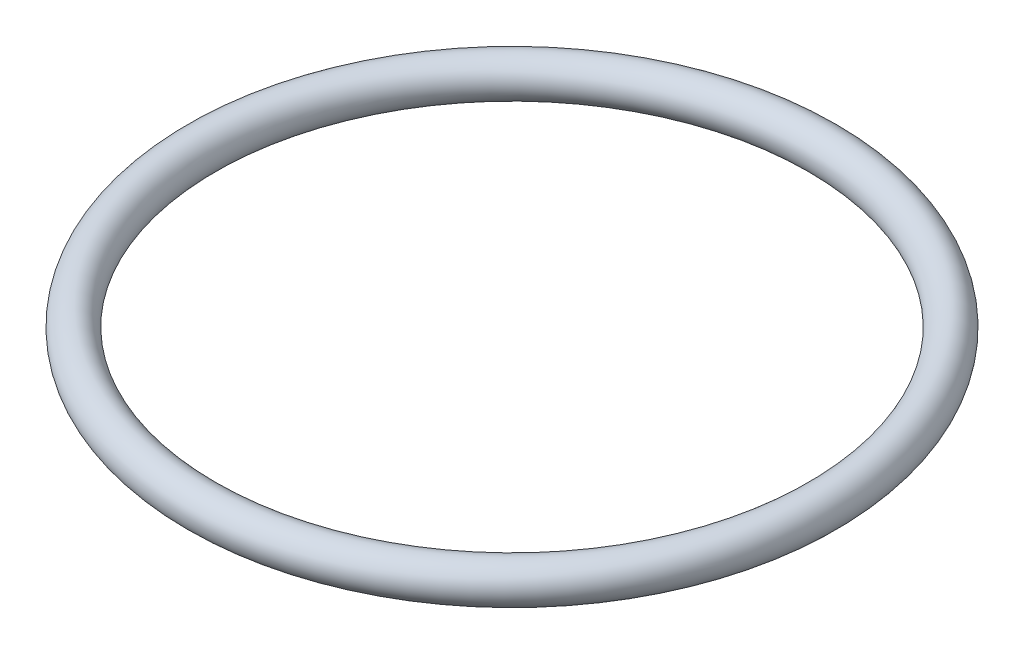
SolidWorks part; units mm, degrees
material "Polybutadiene (PB)"
ref_plane "Front Plane" through (0, 0, 0) normal (0, 0, 1) x (1, 0, 0)
ref_plane "Top Plane" through (0, 0, 0) normal (0, 1, 0) x (1, 0, 0)
ref_plane "Right Plane" through (0, 0, 0) normal (1, 0, 0) x (0, 0, -1)
sketch "Sketch1" plane through (0, 0, 0) normal (0, 0, 1) x (1, 0, 0)
  line L0 (0, 0) -> (0, 69.7559) construction
  line L1 (0, 0) -> (37.5, 0) construction
  circle A0 centre (40, 0) radius 2.5
  dimension "D2" = 5
  dimension "D1" = 37.5
revolve "Revolve1" add sketch "Sketch1" angle 360 about L0
equation "\"D1@Sketch1\"=75.000000/2mm"
